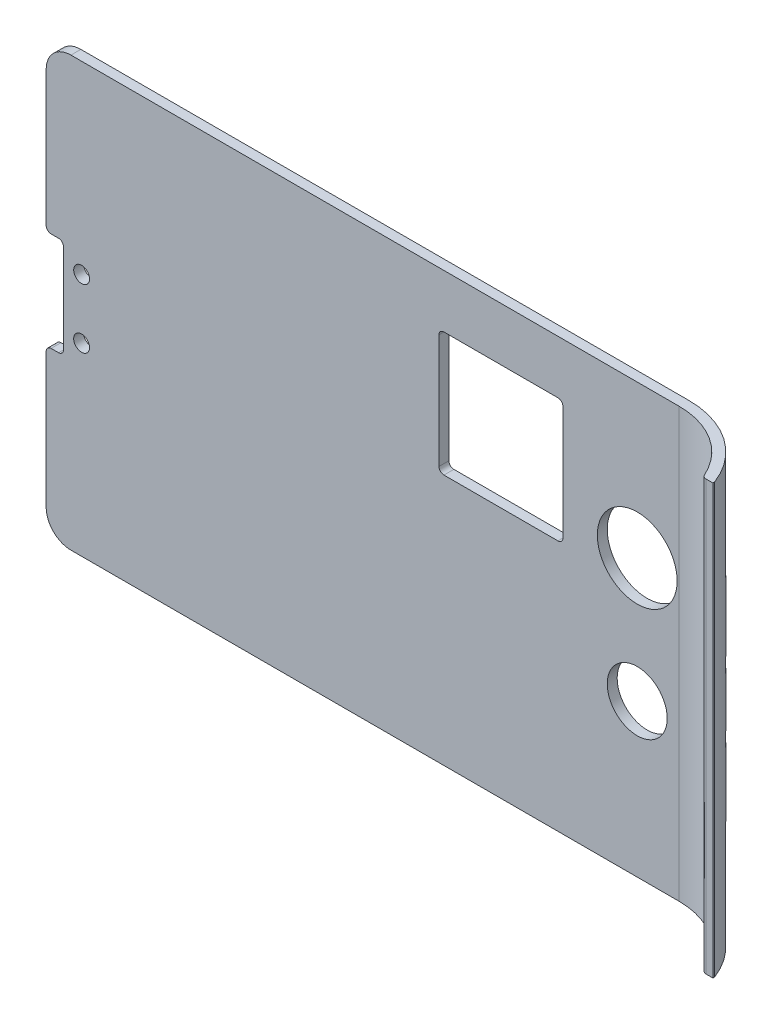
SolidWorks part; units mm, degrees
material "ABS"
ref_plane "前视基准面" through (0, 0, 0) normal (0, 0, 1) x (1, 0, 0)
ref_plane "上视基准面" through (0, 0, 0) normal (0, 1, 0) x (1, 0, 0)
ref_plane "右视基准面" through (0, 0, 0) normal (1, 0, 0) x (0, 0, -1)
other "Configuration Table"
sketch "草图1" plane through (0, 0, 0) normal (0, 0, 1) x (1, 0, 0)
  line L0 (-38.6665, 0) -> (31.2744, 0) construction
  line L1 (0, 22.4607) -> (0, -30.1372) construction
  line L2 (72.25, -38.25) -> (72.25, 38.25)
  line L3 (67.25, 43.25) -> (-67.25, 43.25)
  line L4 (-72.25, 38.25) -> (-72.25, -38.25)
  line L5 (-67.25, -43.25) -> (67.25, -43.25)
  arc A0 (72.25, 38.25) -> (67.25, 43.25) centre (67.25, 38.25) ccw
  arc A1 (-67.25, 43.25) -> (-72.25, 38.25) centre (-67.25, 38.25) ccw
  arc A2 (-72.25, -38.25) -> (-67.25, -43.25) centre (-67.25, -38.25) ccw
  arc A3 (67.25, -43.25) -> (72.25, -38.25) centre (67.25, -38.25) ccw
  dimension "D3" = 5
  dimension "D1" = 144.5
  dimension "D2" = 86.5
extrude "凸台-拉伸1" add sketch "草图1" along normal blind 2
sketch "草图3" plane through (0, 0, 0) normal (0, 1, 0) x (1, 0, 0)
  line L0 (55.4176, 0) -> (55.4176, -2)
  line L5 (67.25, 0) -> (-67.25, 0) construction
  line L6 (67.25, -2) -> (-67.25, -2) construction
  line L7 (70.25, -12) -> (72.25, -12)
  line L8 (72.25, -12) -> (72.25, -11.6227)
  line L9 (72.25, -2) -> (72.25, 0) construction
  arc A2 (55.4176, 0) -> (72.25, -11.6227) centre (55.4176, -18) cw
  arc A3 (55.4176, -2) -> (70.25, -12) centre (55.4176, -18) cw
  dimension "D1" = 2
  dimension "D2" = 12
  dimension "D3" = 18
extrude "凸台-拉伸2" add sketch "草图3" along normal up to surface and the other way up to surface up to face at (0, 43.25, 1) other way up to face at (0, -43.25, 1)
sketch "草图6" plane through (0, 43.25, 0) normal (0, 1, 0) x (1, 0, 0)
  line L0 (67.25, 0) -> (-67.25, 0) construction
  line L1 (55.4176, 0) -> (72.25, 0)
  line L2 (72.25, 0) -> (72.25, -2)
  line L3 (72.25, -2) -> (63.6638, -2)
  arc A1 (63.6638, -2) -> (55.4176, 0) centre (55.4176, -18) ccw
  arc A2 (72.25, -11.6227) -> (63.6638, -2) centre (55.4176, -18) ccw construction
extrude "切除-拉伸2" cut sketch "草图6" against normal through all
fillet "圆角2" radius 1 1 edges at (70.25, 0, 12)
sketch "草图7" plane through (0, -43.25, 0) normal (0, -1, 0) x (1, 0, 0)
  line L0 (58.5502, -4.3233) -> (80.5075, 17.6341) construction
  line L1 (-67.25, 0) -> (55.4176, 0) construction
  arc A0 (55.4176, 0) -> (72.25, 11.6227) centre (55.4176, 18) ccw construction
  point P7 (68.1455, 5.2721)
  dimension "D1" = 45
ref_plane "基准面1" through (31.4367, 0, -31.4367) normal (0.7071, 0, -0.7071) x (-0.7071, 0, -0.7071)
sketch "草图8" plane through (31.4367, 0, -31.4367) normal (0.7071, 0, -0.7071) x (-0.7071, 0, -0.7071)
  line L0 (-51.9141, -43.25) -> (-51.9141, 79.2074) construction
  line L4 (-90.9242, 0) -> (59.8228, 0) construction
  circle A0 centre (-51.9141, 6.5) radius 1.6
  circle A1 centre (-51.9141, -6.5) radius 1.6
  dimension "D1" = 13
  dimension "D2" = 3.2
extrude "切除-拉伸3" cut sketch "草图8" against normal through all
sketch "草图10" plane through (0, 0, 0) normal (0, 0, -1) x (-1, 0, 0)
  line L1 (72.25, 38.25) -> (72.25, -38.25) construction
  line L3 (0, 0) -> (140.8443, 0) construction
  line L5 (72.25, -10) -> (68.75, -10)
  line L6 (72.25, -10) -> (72.25, 10)
  line L7 (72.25, 10) -> (68.75, 10)
  line L8 (68.75, -10) -> (68.75, 10)
  circle A2 centre (65.1, 6) radius 1.6
  circle A3 centre (65.1, -6) radius 1.6
  dimension "D1" = 7.15
  dimension "D2" = 12
  dimension "D3" = 3.2
  dimension "D4" = 20
  dimension "D5" = 3.5
extrude "切除-拉伸5" cut sketch "草图10" against normal through all
sketch "草图11" plane through (0, 0, 0) normal (0, 0, -1) x (-1, 0, 0)
  line L0 (-101.7093, 0) -> (109.62, 0) construction
  circle A0 centre (-47, 12.5) radius 8.05
  circle A1 centre (-47, -12.5) radius 6.05
  dimension "D1" = 16.1
  dimension "D2" = 12.1
  dimension "D4" = 25
  dimension "D3" = 47
extrude "切除-拉伸6" cut sketch "草图11" against normal through all
sketch "草图12" plane through (0, 0, 0) normal (0, 0, -1) x (-1, 0, 0)
  line L1 (-7, 7.5) -> (-32, 7.5)
  line L2 (-7, 7.5) -> (-7, 32.5)
  line L3 (-7, 32.5) -> (-32, 32.5)
  line L4 (-32, 7.5) -> (-32, 32.5)
  dimension "D1" = 7.5
  dimension "D2" = 25
  dimension "D3" = 25
  dimension "D4" = 32
extrude "切除-拉伸7" cut sketch "草图12" against normal through all
fillet "圆角3" radius 1 8 edges at (-68.75, -10, 1) (-68.75, 10, 1) (-72.25, -10, 1) (-72.25, 10, 1) (32, 7.5, 1) (7, 7.5, 1) (7, 32.5, 1) (32, 32.5, 1)
